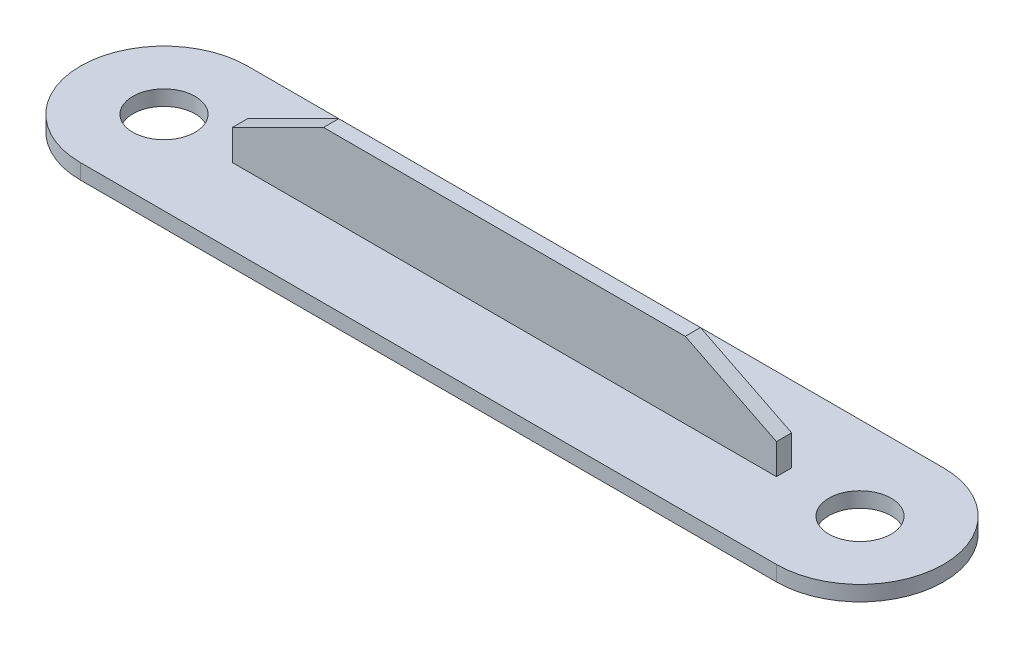
SolidWorks part; units mm, degrees
ref_plane "前视基准面" through (0, 0, 0) normal (0, 0, 1) x (1, 0, 0)
ref_plane "上视基准面" through (0, 0, 0) normal (0, 1, 0) x (1, 0, 0)
ref_plane "右视基准面" through (0, 0, 0) normal (1, 0, 0) x (0, 0, -1)
sketch "草图4" plane through (0, 0, 0) normal (0, 1, 0) x (1, 0, 0)
  line L0 (-1000, 0) -> (49000, 0) construction
  line L1 (0, -1000) -> (0, 49000) construction
  line L2 (-229, 55) -> (229, 55)
  line L3 (-229, -55) -> (229, -55)
  circle A0 centre (-229, 0) radius 20.5
  circle A1 centre (229, 0) radius 20.5
  arc A2 (-229, 55) -> (-229, -55) centre (-229, 0) ccw
  arc A3 (229, 55) -> (229, -55) centre (229, 0) cw
  dimension "D1" = 458
  dimension "D2" = 41
  dimension "D3" = 110
extrude "凸台-拉伸4" add sketch "草图4" along normal blind 10
sketch "草图5" plane through (0, 10, 0) normal (0, 1, 0) x (1, 0, 0)
  line L0 (-229, 0) -> (49771, 0) construction
  line L1 (0, -1000) -> (0, 49000) construction
  line L2 (-179, 5) -> (179, 5)
  line L3 (-179, 5) -> (-179, -5)
  line L4 (-179, -5) -> (179, -5)
  line L5 (179, 5) -> (179, -5)
  dimension "D1" = 10
  dimension "D2" = 358
extrude "凸台-拉伸5" add sketch "草图5" along normal blind 50
sketch "草图6" plane through (0, 0, 5) normal (0, 0, 1) x (1, 0, 0)
  line L0 (-179, 60) -> (-179, 30)
  line L1 (-179, 60) -> (-179, 10) construction
  line L2 (-179, 30) -> (-119, 60)
  line L3 (-179, 60) -> (179, 60) construction
  line L4 (-119, 60) -> (-179, 60)
  line L5 (179, 60) -> (179, 30)
  line L6 (179, 60) -> (179, 10) construction
  line L7 (179, 30) -> (119, 60)
  line L8 (119, 60) -> (179, 60)
  line L9 (-179, 10) -> (179, 10) construction
  dimension "D1" = 20
  dimension "D2" = 20
  dimension "D3" = 238
extrude "切除-拉伸1" cut sketch "草图6" against normal through all
